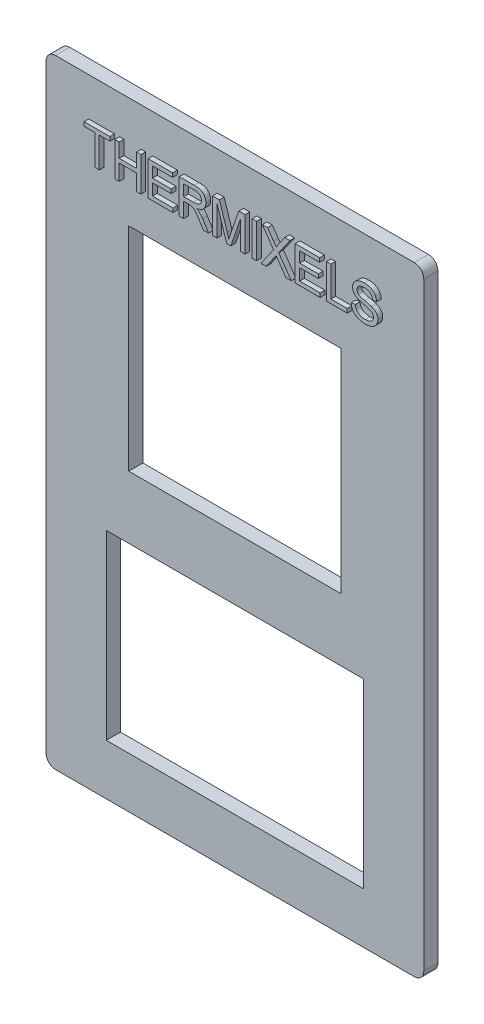
SolidWorks part; units mm, degrees
ref_plane "Front Plane" through (0, 0, 0) normal (0, 0, 1) x (1, 0, 0)
ref_plane "Top Plane" through (0, 0, 0) normal (0, 1, 0) x (1, 0, 0)
ref_plane "Right Plane" through (0, 0, 0) normal (1, 0, 0) x (0, 0, -1)
sketch "Sketch1" plane through (0, 0, 0) normal (0, 0, 1) x (1, 0, 0)
  line L1 (0, 0) -> (80, 0)
  line L2 (0, 0) -> (0, 131)
  line L3 (0, 131) -> (80, 131)
  line L4 (80, 0) -> (80, 131)
  line L5 (62.5, 62.5) -> (17.5, 62.5)
  line L6 (62.5, 62.5) -> (62.5, 107.5)
  line L7 (62.5, 107.5) -> (17.5, 107.5)
  line L8 (17.5, 62.5) -> (17.5, 107.5)
  line L9 (62.5, 62.5) -> (17.5, 107.5) construction
  line L10 (62.5, 107.5) -> (17.5, 62.5) construction
  line L11 (12.75, 49.25) -> (67.25, 49.25)
  line L12 (12.75, 49.25) -> (12.75, 10.75)
  line L13 (12.75, 10.75) -> (67.25, 10.75)
  line L14 (67.25, 49.25) -> (67.25, 10.75)
  line L15 (12.75, 49.25) -> (67.25, 10.75) construction
  line L16 (12.75, 10.75) -> (67.25, 49.25) construction
  point P5 (40, 85)
  point P10 (40, 30)
  point P15 (40, 0)
  point P16 (0, 0)
  dimension "D1" = 131
  dimension "D2" = 80
  dimension "D3" = 38.5
  dimension "D4" = 54.5
  dimension "D5" = 45
  dimension "D6" = 45
  dimension "D7" = 30
  dimension "D8" = 85
extrude "Boss-Extrude1" add sketch "Sketch1" along normal blind 3
sketch "Sketch2" plane through (0, 0, 3) normal (0, 0, 1) x (1, 0, 0)
  line L0 (40, 107.5) -> (40, 131) construction
  line L1 (62.5, 107.5) -> (17.5, 107.5) construction
  line L2 (80, 131) -> (0, 131) construction
  line L4 (72.2691, 115.625) -> (7.7309, 115.625) construction
  line L5 (72.2691, 115.625) -> (72.2691, 122.875) construction
  line L6 (72.2691, 122.875) -> (7.7309, 122.875) construction
  line L7 (7.7309, 115.625) -> (7.7309, 122.875) construction
  line L8 (72.2691, 115.625) -> (7.7309, 122.875) construction
  line L9 (72.2691, 122.875) -> (7.7309, 115.625) construction
  text T0 "THERMIXELS" font "Arial Narrow" height 7.25
  point P1 (40, 119.25)
  point P12 (35.0113, 117.4378)
  point P13 (59.0117, 119.9178)
  point P14 (40, 119.25)
  point P15 (11.011, 115.625)
  point P16 (0, 0)
  point P17 (0, 0)
  dimension "D1" = 7.25
extrude "Boss-Extrude2" add sketch "Sketch2" along normal blind 1
fillet "Fillet1" radius 2 4 edges at (0, 0, 1.5) (80, 0, 1.5) (80, 131, 1.5) (0, 131, 1.5)
